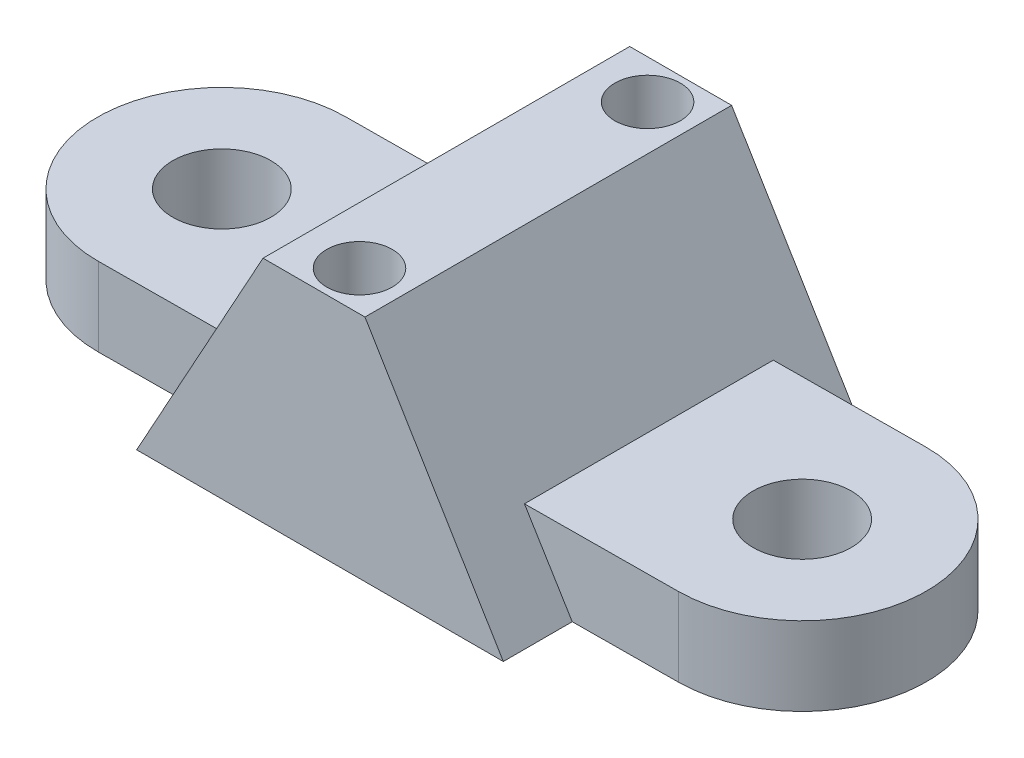
SolidWorks part; units mm, degrees
ref_plane "정면" through (0, 0, 0) normal (0, 0, 1) x (1, 0, 0)
ref_plane "윗면" through (0, 0, 0) normal (0, 1, 0) x (1, 0, 0)
ref_plane "우측면" through (0, 0, 0) normal (1, 0, 0) x (0, 0, -1)
sketch "스케치1" plane through (0, 0, 0) normal (0, 0, 1) x (1, 0, 0)
  line L0 (-28, 0) -> (28, 0)
  line L1 (28, 0) -> (6.8659, 35)
  line L2 (6.8659, 35) -> (-8.6988, 35)
  line L3 (-8.6988, 35) -> (-28, 0)
  point P3 (-10.1017, 35)
  point P6 (26.4777, 35)
  point P7 (11.9341, 35)
  point P8 (-14.2885, 35)
  point P9 (0, 0)
  point P10 (0, 0)
  point P11 (0, 0)
  point P12 (6.8659, 35)
  point P13 (-10.322, 35)
  point P14 (0, 0)
  point P15 (0, 0)
  point P16 (11.7138, 35)
  point P17 (0, 0)
  point P18 (0, 0)
  point P19 (0, 0)
  point P20 (5.3234, 35)
  point P21 (6.8659, 35)
  dimension "D1" = 35
  dimension "D2" = 56
  dimension "D3" = 60
extrude "보스-돌출1" add sketch "스케치1" along normal blind 56 contours L3 L0 L1 L2
sketch "스케치3" plane through (0, 0, 0) normal (0, -1, 0) x (1, 0, 0)
  line L0 (-44, 26.9914) -> (44, 26.3603) construction
  line L1 (-43.8637, 45.9909) -> (44.1363, 45.3598)
  line L2 (-44.1363, 7.9919) -> (43.8637, 7.3608)
  arc A0 (-43.8637, 45.9909) -> (-44.1363, 7.9919) centre (-44, 26.9914) ccw
  arc A1 (43.8637, 7.3608) -> (44.1363, 45.3598) centre (44, 26.3603) ccw
  circle A2 centre (-44, 26.9914) radius 7.5
  circle A3 centre (44, 26.3603) radius 7.5
  point P2 (0, 26.6758)
  point P11 (0, 0)
  point P13 (0, 0)
  point P14 (0, 0)
  point P31 (0, 0)
  dimension "D1" = 19
  dimension "D2" = 15
  dimension "D3" = 88
extrude "보스-돌출3" add sketch "스케치3" against normal blind 12
sketch "스케치4" plane through (0, 35, 0) normal (0, 1, 0) x (1, 0, 0)
  circle A2 centre (0, -5.9677) radius 5
  circle A3 centre (0, -49.9677) radius 5
  dimension "D1" = 10
  dimension "D2" = 44
extrude "컷-돌출1" cut sketch "스케치4" against normal through all
